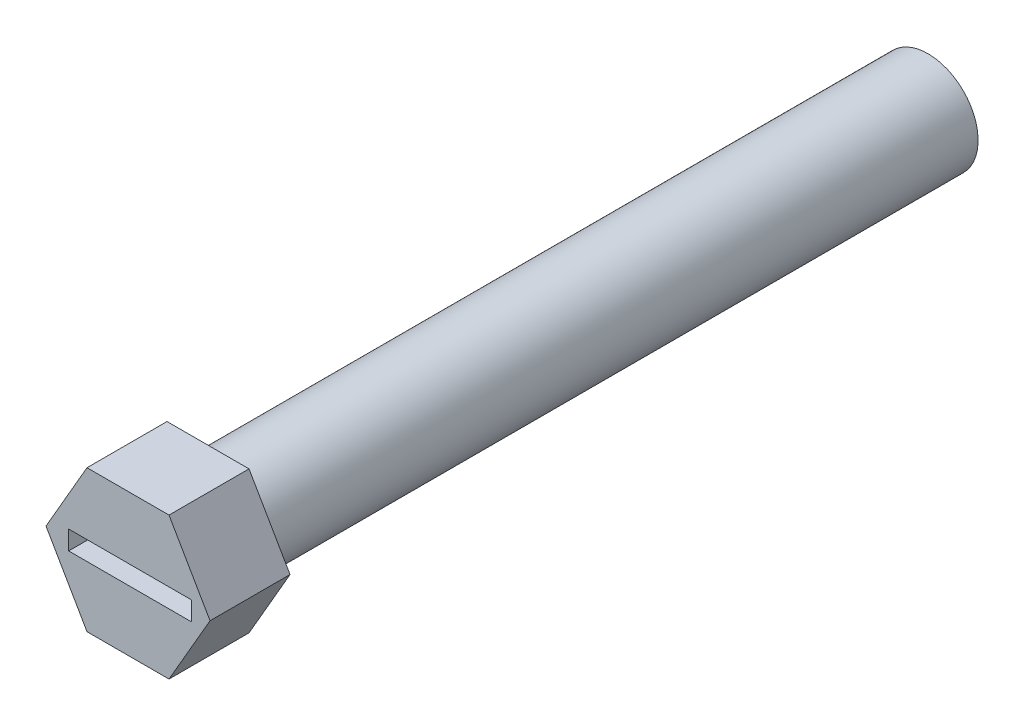
SolidWorks part; units mm, degrees
ref_plane "Front Plane" through (0, 0, 0) normal (0, 0, 1) x (1, 0, 0)
ref_plane "Top Plane" through (0, 0, 0) normal (0, 1, 0) x (1, 0, 0)
ref_plane "Right Plane" through (0, 0, 0) normal (1, 0, 0) x (0, 0, -1)
sketch "Sketch1" plane through (0, 0, 0) normal (0, 0, 1) x (1, 0, 0)
  circle A0 centre (0, 0) radius 12.5
  dimension "D1" = 25
extrude "Boss-Extrude1" add sketch "Sketch1" along normal blind 180
sketch "Sketch2" plane through (0, 0, 180) normal (0, 0, 1) x (1, 0, 0)
  line L1 (20.5012, 0) -> (10.2506, 17.7546)
  line L2 (10.2506, 17.7546) -> (-10.2506, 17.7546)
  line L3 (-10.2506, 17.7546) -> (-20.5012, 0)
  line L4 (-20.5012, 0) -> (-10.2506, -17.7546)
  line L5 (-10.2506, -17.7546) -> (10.2506, -17.7546)
  line L6 (10.2506, -17.7546) -> (20.5012, 0)
  circle A0 centre (0, 0) radius 17.7546 construction
extrude "Boss-Extrude2" add sketch "Sketch2" along normal blind 20
sketch "Sketch3" plane through (0, 0, 200) normal (0, 0, 1) x (1, 0, 0)
  line L1 (-14.8335, 2.1962) -> (15.8416, 2.1962)
  line L2 (-14.8335, 2.1962) -> (-14.8335, -2.5563)
  line L3 (-14.8335, -2.5563) -> (15.8416, -2.5563)
  line L4 (15.8416, 2.1962) -> (15.8416, -2.5563)
extrude "Cut-Extrude1" cut sketch "Sketch3" against normal blind 15
